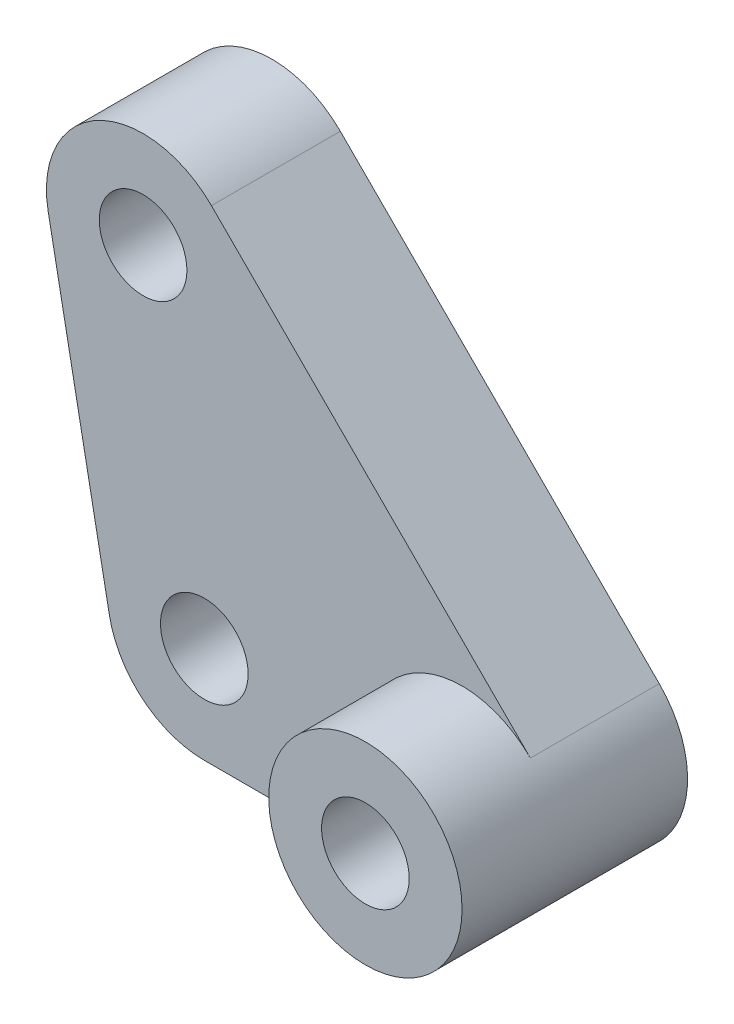
SolidWorks part; units mm, degrees
ref_plane "Front Plane" through (0, 0, 0) normal (0, 0, 1) x (1, 0, 0)
ref_plane "Top Plane" through (0, 0, 0) normal (0, 1, 0) x (1, 0, 0)
ref_plane "Right Plane" through (0, 0, 0) normal (1, 0, 0) x (0, 0, -1)
sketch "Sketch1" plane through (0, 0, 0) normal (0, 0, 1) x (1, 0, 0)
  line L0 (-12.7, 0) -> (0, 0) construction
  line L1 (0, -4.7625) -> (-12.7, -4.7625)
  line L3 (-15.7154, 15.7154) -> (0, 0) construction
  line L5 (3.3676, 3.3676) -> (-12.3479, 19.083)
  line L6 (-20.3926, 14.818) -> (-17.3772, -0.8974)
  line L7 (0, 0) -> (-15.7154, 15.7154) construction
  arc A0 (0, -4.7625) -> (3.3676, 3.3676) centre (0, 0) ccw
  arc A1 (-17.3772, -0.8974) -> (-12.7, -4.7625) centre (-12.7, 0) ccw
  arc A3 (-12.3479, 19.083) -> (-20.3926, 14.818) centre (-15.7154, 15.7154) ccw
  circle A4 centre (-12.7, 0) radius 2.159
  circle A5 centre (-15.7154, 15.7154) radius 2.159
  circle A6 centre (0, 0) radius 2.159
  dimension "D3" = 4.318
  dimension "D4" = 4.7625
  dimension "D5" = 4.7625
  dimension "D6" = 4.7625
  dimension "D1" = 12.7
  dimension "D2" = 22.225
  dimension "D7" = 45
extrude "Boss-Extrude1" add sketch "Sketch1" along normal mid plane 6.35
sketch "Sketch3" plane through (0, 0, 3.175) normal (0, 0, 1) x (1, 0, 0)
  circle A0 centre (0, 0) radius 4.7625
  circle A1 centre (0, 0) radius 2.159 construction
  circle A2 centre (0, 0) radius 2.159
extrude "Boss-Extrude2" add sketch "Sketch3" along normal mid plane 9.525
